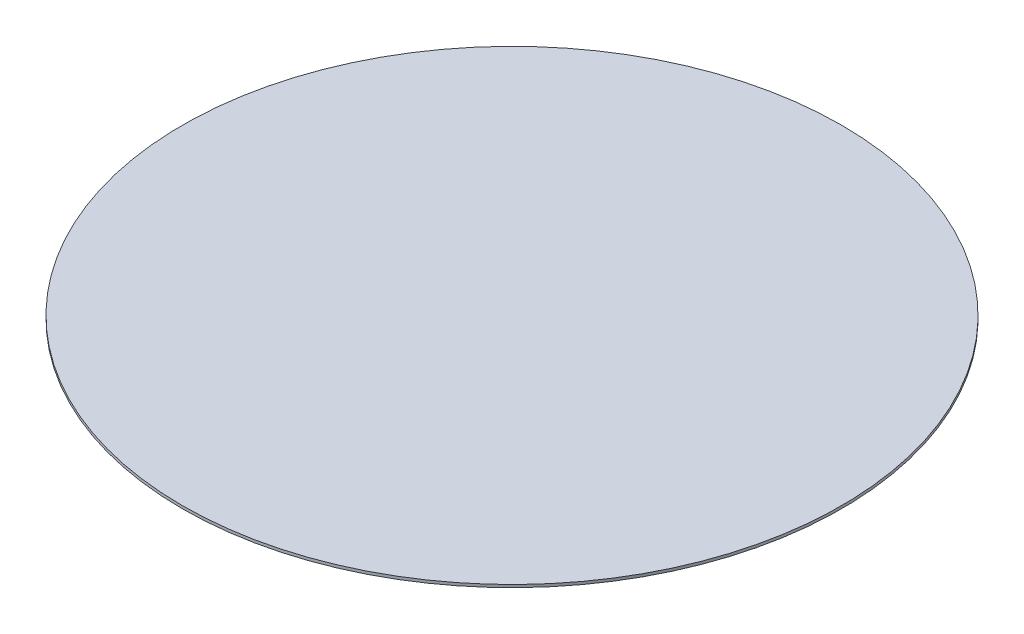
SolidWorks part; units mm, degrees
ref_plane "Front Plane" through (0, 0, 0) normal (0, 0, 1) x (1, 0, 0)
ref_plane "Top Plane" through (0, 0, 0) normal (0, 1, 0) x (1, 0, 0)
ref_plane "Right Plane" through (0, 0, 0) normal (1, 0, 0) x (0, 0, -1)
sketch "Sketch1" plane through (0, 0, 0) normal (0, 1, 0) x (1, 0, 0)
  circle A0 centre (0, 0) radius 95.25
  dimension "D1" = 190.5
extrude "Boss-Extrude1" add sketch "Sketch1" along normal blind 0.7937 contours A0
